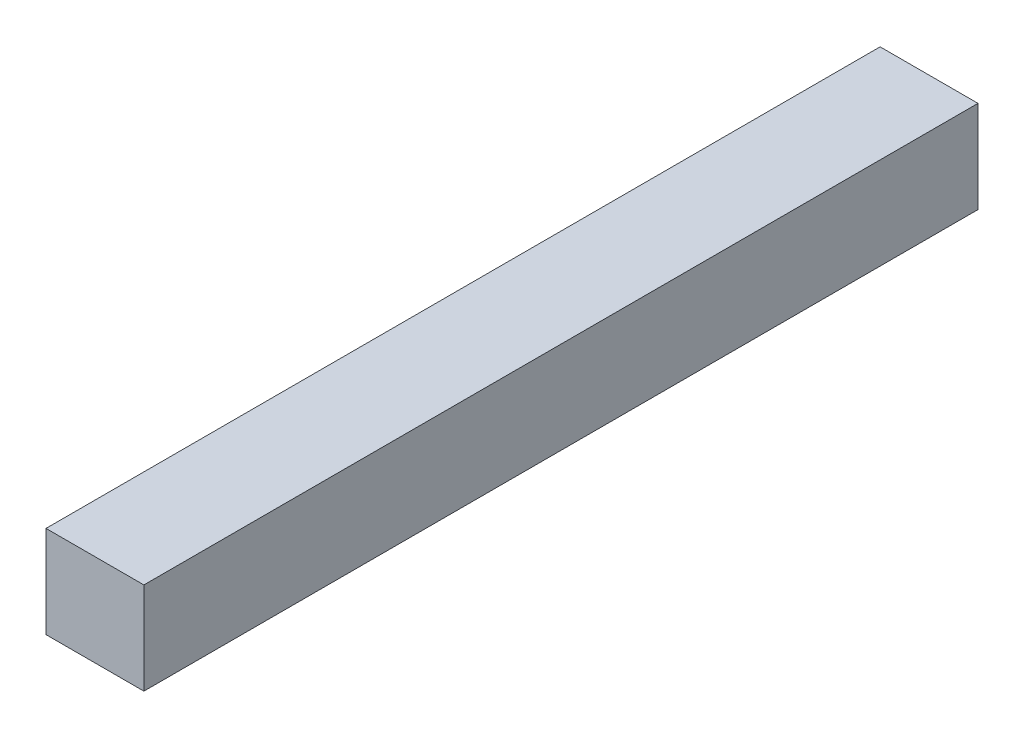
SolidWorks part; units mm, degrees
ref_plane "Front Plane" through (0, 0, 0) normal (0, 0, 1) x (1, 0, 0)
ref_plane "Top Plane" through (0, 0, 0) normal (0, 1, 0) x (1, 0, 0)
ref_plane "Right Plane" through (0, 0, 0) normal (1, 0, 0) x (0, 0, -1)
sketch "Sketch1" plane through (0, 0, 0) normal (0, 0, 1) x (1, 0, 0)
  line L1 (-25.0819, 18.7097) -> (24.9181, 18.7097)
  line L2 (-25.0819, 18.7097) -> (-25.0819, -28.2903)
  line L3 (-25.0819, -28.2903) -> (24.9181, -28.2903)
  line L4 (24.9181, 18.7097) -> (24.9181, -28.2903)
  dimension "D1" = 50
  dimension "D2" = 47
extrude "Boss-Extrude1" add sketch "Sketch1" along normal blind 426
